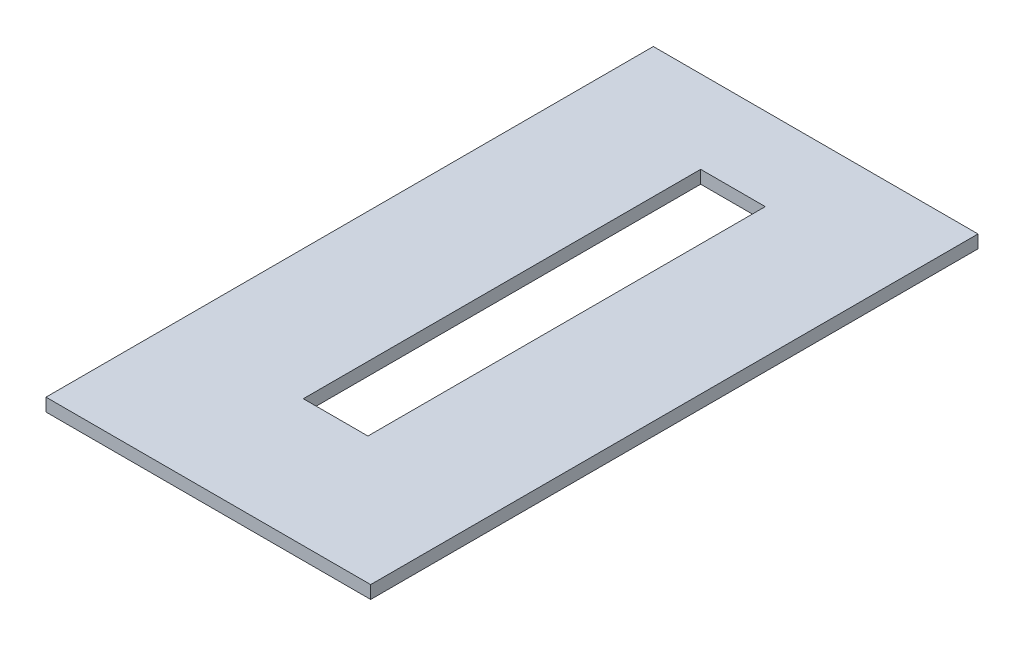
SolidWorks part; units mm, degrees
material "Бетон М200"
ref_plane "Спереди" through (0, 0, 0) normal (0, 0, 1) x (1, 0, 0)
ref_plane "Сверху" through (0, 0, 0) normal (0, 1, 0) x (1, 0, 0)
ref_plane "Справа" through (0, 0, 0) normal (1, 0, 0) x (0, 0, -1)
sketch "Эскиз1" plane through (0, 0, 0) normal (0, 1, 0) x (1, 0, 0)
  line L0 (-2512.5, -4700) -> (2512.5, -4700) construction
  line L1 (-2512.5, 4700) -> (2512.5, 4700)
  line L2 (-2512.5, 4700) -> (-2512.5, -4700)
  line L3 (-2512.5, -4700) -> (2512.5, -4700)
  line L4 (2512.5, 4700) -> (2512.5, -4700)
  line L5 (2512.5, -4700) -> (2512.5, 4700) construction
  line L6 (-2512.5, 4700) -> (-2512.5, -4700) construction
  line L7 (2512.5, 4700) -> (-2512.5, 4700) construction
  line L9 (-500, 3420) -> (500, 3420)
  line L10 (-500, 3420) -> (-500, -2730)
  line L11 (-500, -2730) -> (500, -2730)
  line L12 (500, 3420) -> (500, -2730)
extrude "Бобышка-Вытянуть1" add sketch "Эскиз1" against normal up to surface (200 mm away)
